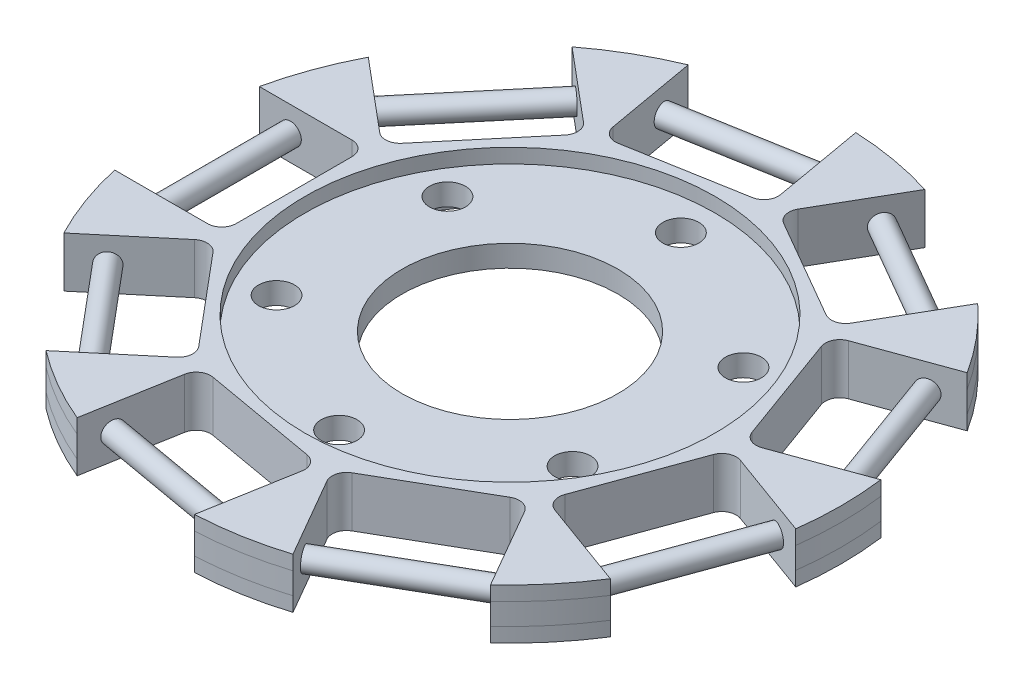
SolidWorks part; units mm, degrees
ref_plane "正面" through (0, 0, 0) normal (0, 0, 1) x (1, 0, 0)
ref_plane "平面" through (0, 0, 0) normal (0, 1, 0) x (1, 0, 0)
ref_plane "右側面" through (0, 0, 0) normal (1, 0, 0) x (0, 0, -1)
sketch "ｽｹｯﾁ1" plane through (0, 0, 0) normal (0, 0, 1) x (1, 0, 0)
  line L0 (0, 0) -> (0, 65.6982) construction
  line L1 (-15, -3.4846) -> (-15, -0.4846)
  line L2 (-15, -0.4846) -> (-28.5, -0.4846)
  line L3 (-28.5, -0.4846) -> (-28.5, 1.5154)
  line L4 (-28.5, 1.5154) -> (-46, 1.5154)
  line L5 (-46, 1.5154) -> (-46, -0.4846)
  line L6 (-46, -5.4846) -> (-28.5, -5.4846)
  line L7 (-28.5, -5.4846) -> (-28.5, -3.4846)
  line L8 (-28.5, -3.4846) -> (-15, -3.4846)
  line L9 (-46, -0.4846) -> (-45.9999, -0.4846)
  line L10 (-45.9999, -0.4846) -> (-45.9999, -3.4846)
  line L11 (-45.9999, -3.4846) -> (-46, -3.4846)
  line L12 (-46, -3.4846) -> (-46, -5.4846)
  dimension "D1" = 15
  dimension "D2" = 28.5
  dimension "D3" = 3
  dimension "D4" = 7
  dimension "D5" = 2
  dimension "D6" = 17.5
  dimension "D7" = 3
  dimension "D8" = 2
  dimension "D9" = 0.0001
revolve "回転1" add sketch "ｽｹｯﾁ1" angle 360 about L0
sketch "ｽｹｯﾁ2" plane through (0, -0.4846, 0) normal (0, 1, 0) x (1, 0, 0)
  circle A0 centre (0, 23.75) radius 2.5
  circle A1 centre (20.5681, 11.875) radius 2.5
  circle A2 centre (20.5681, -11.875) radius 2.5
  circle A3 centre (0, -23.75) radius 2.5
  circle A4 centre (-20.5681, -11.875) radius 2.5
  circle A5 centre (-20.5681, 11.875) radius 2.5
  point P16 (0, 0)
  dimension "D1" = 23.75
  dimension "D2" = 5
  dimension "D3" = 6
extrude "ｶｯﾄ - 押し出し1" cut sketch "ｽｹｯﾁ2" against normal blind 10
sketch "ｽｹｯﾁ3" plane through (0, 1.5154, 0) normal (0, 1, 0) x (1, 0, 0)
  line L1 (0, 23.75) -> (20.5681, 11.875) construction
  line L2 (21.9715, 21.9558) -> (8.0285, 30.0058)
  line L3 (24.7036, 22.6878) -> (38.5557, 46.6805)
  line L4 (7.2964, 32.7378) -> (21.1486, 56.7305)
  line L5 (38.5557, 46.6805) -> (21.1486, 56.7305)
  line L6 (23.7036, 20.9558) -> (21.1486, 56.7305) construction
  line L7 (6.2964, 31.0058) -> (38.5557, 46.6805) construction
  line L8 (33.5075, 1.5007) -> (59.5411, 10.9762)
  line L9 (30.944, 2.6961) -> (25.4375, 17.8251)
  line L10 (26.6329, 20.3886) -> (52.6665, 29.864)
  line L11 (59.5411, 10.9762) -> (52.6665, 29.864)
  line L12 (26.6329, -20.3886) -> (52.6665, -29.864)
  line L13 (25.4375, -17.8251) -> (30.944, -2.6961)
  line L14 (33.5075, -1.5007) -> (59.5411, -10.9762)
  line L15 (52.6665, -29.864) -> (59.5411, -10.9762)
  line L16 (7.2964, -32.7378) -> (21.1486, -56.7305)
  line L17 (8.0285, -30.0058) -> (21.9715, -21.9558)
  line L18 (24.7036, -22.6878) -> (38.5557, -46.6805)
  line L19 (21.1486, -56.7305) -> (38.5557, -46.6805)
  line L20 (-15.4541, -29.7687) -> (-20.2649, -57.0522)
  line L21 (-13.1371, -28.1464) -> (2.7183, -30.9421)
  line L22 (4.3406, -33.259) -> (-0.4702, -60.5425)
  line L23 (-20.2649, -57.0522) -> (-0.4702, -60.5425)
  line L24 (-30.9734, -12.8705) -> (-52.1962, -30.6785)
  line L25 (-28.1558, -13.117) -> (-17.8069, -25.4503)
  line L26 (-18.0534, -28.268) -> (-39.2762, -46.076)
  line L27 (-52.1962, -30.6785) -> (-39.2762, -46.076)
  line L28 (-32, 10.05) -> (-59.7044, 10.05)
  line L29 (-30, 8.05) -> (-30, -8.05)
  line L30 (-32, -10.05) -> (-59.7044, -10.05)
  line L31 (-59.7044, 10.05) -> (-59.7044, -10.05)
  line L32 (-18.0534, 28.268) -> (-39.2762, 46.076)
  line L33 (-17.8069, 25.4503) -> (-28.1558, 13.117)
  line L34 (-30.9734, 12.8705) -> (-52.1962, 30.6785)
  line L35 (-39.2762, 46.076) -> (-52.1962, 30.6785)
  line L36 (4.3406, 33.259) -> (-0.4702, 60.5425)
  line L37 (2.7183, 30.9421) -> (-13.1371, 28.1464)
  line L38 (-15.4541, 29.7687) -> (-20.2649, 57.0522)
  line L39 (-0.4702, 60.5425) -> (-20.2649, 57.0522)
  circle A1 centre (0, 0) radius 28.5 construction
  circle A2 centre (0, 0) radius 46
  circle A3 centre (0, 0) radius 46
  arc A4 (4.3406, 33.259) -> (2.7183, 30.9421) centre (2.371, 32.9117) cw
  arc A5 (-13.1371, 28.1464) -> (-15.4541, 29.7687) centre (-13.4844, 30.116) cw
  arc A6 (-18.0534, 28.268) -> (-17.8069, 25.4503) centre (-19.339, 26.7359) cw
  arc A7 (-28.1558, 13.117) -> (-30.9734, 12.8705) centre (-29.6879, 14.4025) cw
  arc A8 (-32, 10.05) -> (-30, 8.05) centre (-32, 8.05) cw
  arc A9 (-30, -8.05) -> (-32, -10.05) centre (-32, -8.05) cw
  arc A10 (-30.9734, -12.8705) -> (-28.1558, -13.117) centre (-29.6879, -14.4025) cw
  arc A11 (-17.8069, -25.4503) -> (-18.0534, -28.268) centre (-19.339, -26.7359) cw
  arc A12 (-15.4541, -29.7687) -> (-13.1371, -28.1464) centre (-13.4844, -30.116) cw
  arc A13 (2.7183, -30.9421) -> (4.3406, -33.259) centre (2.371, -32.9117) cw
  arc A14 (7.2964, -32.7378) -> (8.0285, -30.0058) centre (9.0285, -31.7378) cw
  arc A15 (21.9715, -21.9558) -> (24.7036, -22.6878) centre (22.9715, -23.6878) cw
  arc A16 (26.6329, -20.3886) -> (25.4375, -17.8251) centre (27.3169, -18.5092) cw
  arc A17 (30.944, -2.6961) -> (33.5075, -1.5007) centre (32.8234, -3.3801) cw
  arc A18 (33.5075, 1.5007) -> (30.944, 2.6961) centre (32.8234, 3.3801) cw
  arc A19 (25.4375, 17.8251) -> (26.6329, 20.3886) centre (27.3169, 18.5092) cw
  arc A20 (24.7036, 22.6878) -> (21.9715, 21.9558) centre (22.9715, 23.6878) cw
  arc A21 (8.0285, 30.0058) -> (7.2964, 32.7378) centre (9.0285, 31.7378) cw
  point P9 (22.4261, 38.8431)
  point P13 (15, 25.9808)
  point P51 (0, 0)
  circle M46 centre (0, 0) radius 46
  dimension "D1" = 2
  dimension "D3" = 0
  dimension "D6" = 20.1
  dimension "D7" = 30
  dimension "D2" = 0
  dimension "D8" = 9
extrude "ｶｯﾄ - 押し出し3" cut sketch "ｽｹｯﾁ3" against normal blind 10 contours A5 L37 A4 L36 L38 M46 | A21 L2 A20 L3 L4 M46 | A19 L9 A18 L8 L10 M46 | A17 L13 A16 L12 L14 M46 | A15 L17 A14 L16 L18 M46 | A13 L21 A12 L20 L22 M46 | A11 L25 A10 L24 L26 M46 | A9 L29 A8 L28 L30 M46 | A7 L33 A6 L32 L34 M46
sketch "ｽｹｯﾁ4" plane through (0, 1.5154, 0) normal (0, 1, 0) x (1, 0, 0)
  line L0 (-16.9388, 38.1888) -> (2.8559, 41.6791) construction
  line L3 (-15.4541, 29.7687) -> (-17.6922, 42.4616) construction
  line L4 (4.3406, 33.259) -> (2.1025, 45.9519) construction
  line L5 (11.5714, 40.1423) -> (28.9786, 30.0923) construction
  line L6 (34.6672, 23.3128) -> (41.5418, 4.425) construction
  line L7 (41.5418, -4.425) -> (34.6672, -23.3128) construction
  line L8 (28.9786, -30.0923) -> (11.5714, -40.1423) construction
  line L9 (2.8559, -41.6791) -> (-16.9388, -38.1888) construction
  line L10 (-24.6031, -33.7638) -> (-37.5231, -18.3663) construction
  line L11 (-40.55, -10.05) -> (-40.55, 10.05) construction
  line L12 (-37.5231, 18.3663) -> (-24.6031, 33.7638) construction
  point P26 (0, 0)
  dimension "D1" = 40.55
  dimension "D2" = 9
sketch "ｽｹｯﾁ5" plane through (-9.8973, 0, 1.7452) normal (0.9848, 0, -0.1736) x (-0.1736, 0, -0.9848)
  line L0 (40.55, 1.5154) -> (40.55, -5.4846) construction
  line L1 (32, -5.4846) -> (44.8887, -5.4846) construction
  circle A0 centre (40.55, -1.9846) radius 1.5
  dimension "D1" = 3
extrude "ﾎﾞｽ - 押し出し1" add sketch "ｽｹｯﾁ5" along normal blind 20.1
sketch3d "3Dｽｹｯﾁ1"
  line L0 (0, 0, 0) -> (0, -7.8348, 0) construction
  point P0 (0, 0, 0)
  point P4 (0, -1.9846, 0)
  dimension "D1" = 1.5
pattern_circular "円形ﾊﾟﾀｰﾝ8" count 9 over 360 about axis through (0, 0, 0) along (0, -1, 0) of "ﾎﾞｽ - 押し出し1"
